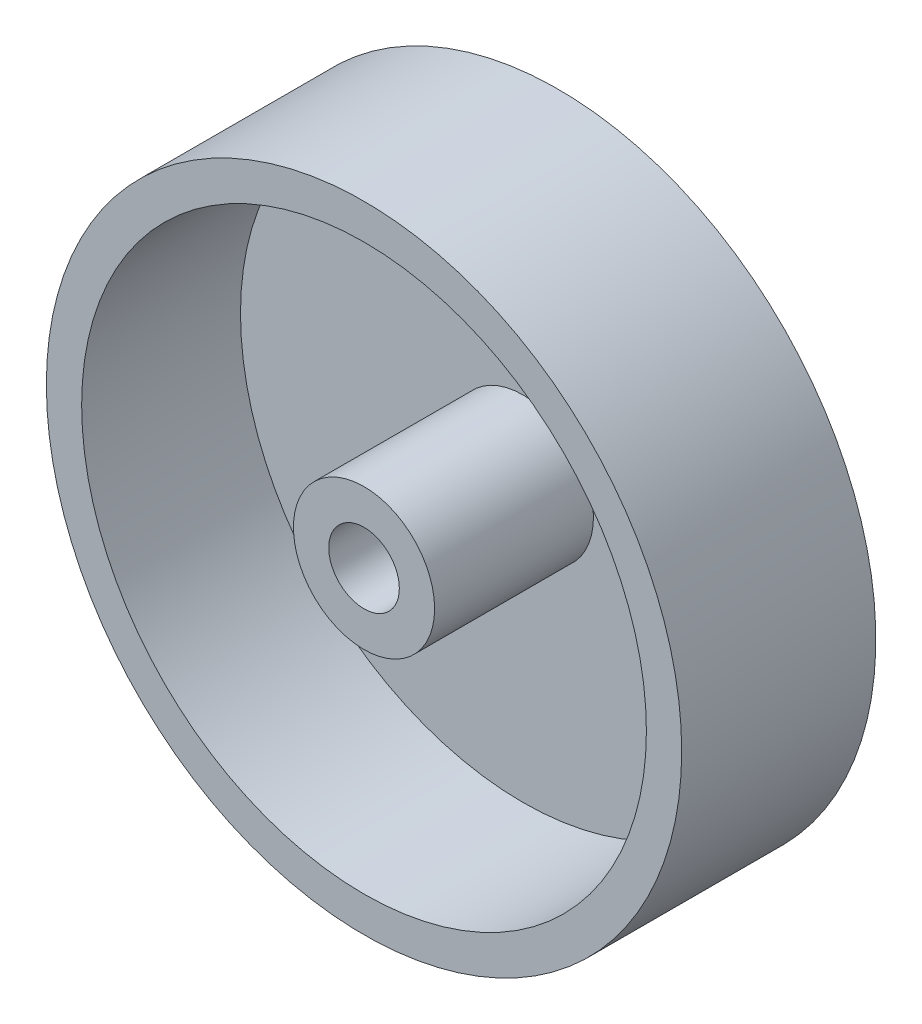
SolidWorks part; units mm, degrees
ref_plane "Front Plane" through (0, 0, 0) normal (0, 0, 1) x (1, 0, 0)
ref_plane "Top Plane" through (0, 0, 0) normal (0, 1, 0) x (1, 0, 0)
ref_plane "Right Plane" through (0, 0, 0) normal (1, 0, 0) x (0, 0, -1)
sketch "Sketch1" plane through (0, 0, 0) normal (0, 0, 1) x (1, 0, 0)
  circle A0 centre (0, 0) radius 88
extrude "Boss-Extrude3" add sketch "Sketch1" along normal blind 25
sketch "Sketch4" plane through (0, 0, 25) normal (0, 0, 1) x (1, 0, 0)
  line L0 (0, 88) -> (0, 100) construction
  line L1 (5.236, 100) -> (-5.236, 100)
  line L2 (-5.236, 100) -> (-5.236, 86.6488)
  line L3 (-5.236, 86.6488) -> (5.236, 86.6488)
  line L4 (5.236, 86.6488) -> (5.236, 100)
  circle A0 centre (0, 0) radius 88 construction
  point P9 (0, 100)
extrude "Boss-Extrude4" add sketch "Sketch4" against normal blind 25
fillet "Fillet2" radius 4 4 edges at (-5.236, 100, 12.5) (0, 100, 0) (5.236, 100, 12.5) (0, 100, 25)
pattern_circular "CirPattern1" count 30 over 360 about axis through (0, 0.3177, 0) along (0, 0, 1) of "Fillet2", "Boss-Extrude4"
ref_plane "Plane1" through (-5.236, 96, 25) normal (-1, 0, 0) x (0, 0, 1)
sketch "Sketch6" plane through (0, 0, 25) normal (0, 0, 1) x (1, 0, 0)
  circle A0 centre (0, 0) radius 10
extrude "Boss-Extrude5" add sketch "Sketch6" along normal blind 60
sketch "Sketch7" plane through (0, 0, 0) normal (0, 0, -1) x (-1, 0, 0)
  circle A0 centre (0, 0) radius 10
extrude "Boss-Extrude6" add sketch "Sketch7" along normal blind 10
sketch "Sketch8" plane through (0, 0, 85) normal (0, 0, 1) x (1, 0, 0)
  circle A0 centre (0, 0) radius 10
extrude "Boss-Extrude7" add sketch "Sketch8" along normal blind 10
sketch "Sketch9" plane through (0, 0, 95) normal (0, 0, 1) x (1, 0, 0)
  circle A0 centre (0, 0) radius 10
extrude "Boss-Extrude8" add sketch "Sketch9" along normal blind 25
sketch "Sketch10" plane through (0, 0, 120) normal (0, 0, 1) x (1, 0, 0)
  circle A0 centre (0, 0) radius 10
extrude "Boss-Extrude9" add sketch "Sketch10" along normal blind 42.5
sketch "Sketch12" plane through (0, 0, 162.5) normal (0, 0, 1) x (1, 0, 0)
  circle A0 centre (0, 0) radius 12.5
extrude "Cut-Extrude1" cut sketch "Sketch12" against normal blind 12
sketch "Sketch13" plane through (0, 0, 150.5) normal (0, 0, 1) x (1, 0, 0)
  circle A0 centre (0, 0) radius 10
extrude "Cut-Extrude2" cut sketch "Sketch13" against normal blind 55.5
sketch "Sketch14" plane through (0, 0, 95) normal (0, 0, 1) x (1, 0, 0)
  circle A0 centre (0, 0) radius 10
extrude "Boss-Extrude10" add sketch "Sketch14" along normal blind 440
sketch "Sketch15" plane through (0, 0, 0) normal (0, 0, -1) x (-1, 0, 0)
  circle A0 centre (0, 0) radius 105
extrude "Boss-Extrude12" add sketch "Sketch15" against normal blind 25
sketch "Sketch16" plane through (0, 0, 0) normal (0, 0, -1) x (-1, 0, 0)
  circle A0 centre (0, 0) radius 105
extrude "Boss-Extrude13" add sketch "Sketch16" along normal blind 30
sketch "Sketch17" plane through (0, 0, 535) normal (0, 0, 1) x (1, 0, 0)
  circle A0 centre (0, 0) radius 10
extrude "Boss-Extrude14" add sketch "Sketch17" along normal blind 50
sketch "Sketch18" plane through (0, 0, 585) normal (0, 0, 1) x (1, 0, 0)
  circle A0 centre (0, 0) radius 10
extrude "Cut-Extrude3" cut sketch "Sketch18" against normal blind 700
sketch "Sketch19" plane through (0, 0, -30) normal (0, 0, -1) x (-1, 0, 0)
  circle A0 centre (0, 0) radius 105
  circle A1 centre (0, 0) radius 90
extrude "Cut-Extrude4" cut sketch "Sketch19" against normal blind 100
shell "Shell1" thickness 10
scale "Scale1" bodies to scale 129 scale about centroid uniform scaling yes scale factor 0.2
